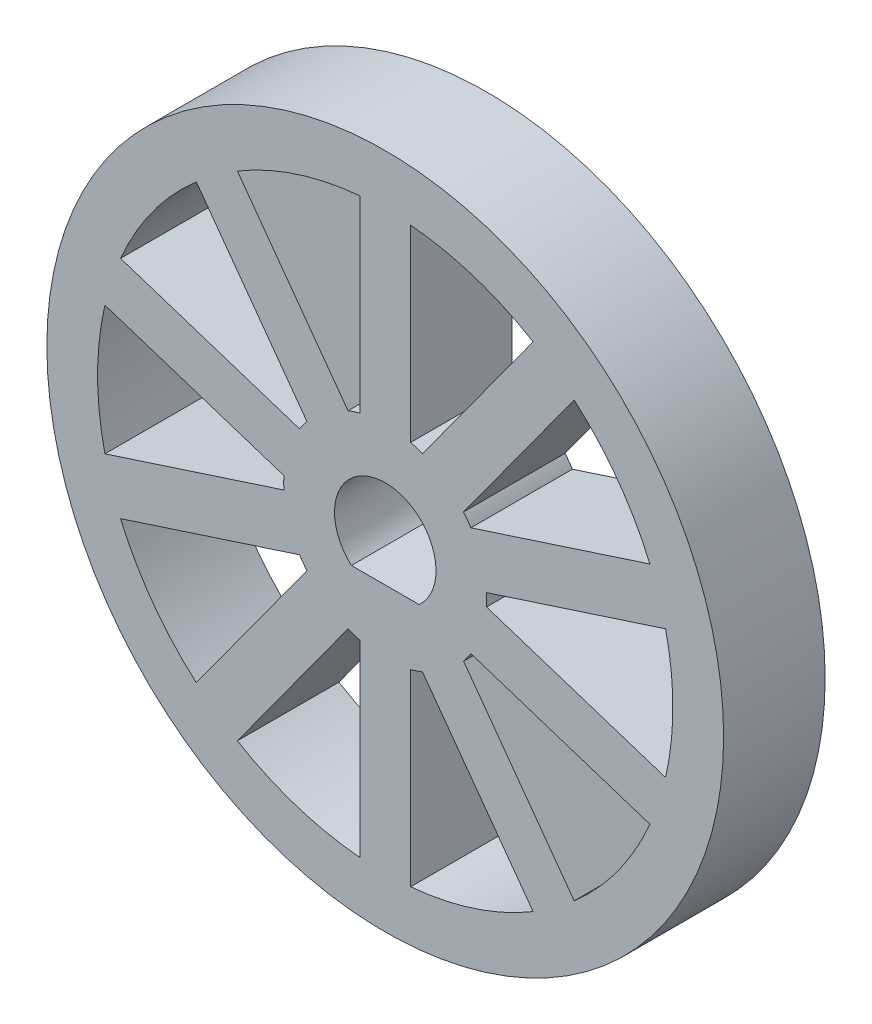
SolidWorks part; units mm, degrees
ref_plane "Front Plane" through (0, 0, 0) normal (0, 0, 1) x (1, 0, 0)
ref_plane "Top Plane" through (0, 0, 0) normal (0, 1, 0) x (1, 0, 0)
ref_plane "Right Plane" through (0, 0, 0) normal (1, 0, 0) x (0, 0, -1)
sketch "Sketch1" plane through (0, 0, 0) normal (0, 0, 1) x (1, 0, 0)
  line L0 (-2, -2.2361) -> (2, -2.2361)
  line L1 (-16.5684, -3.8062) -> (-5.9887, -0.3686)
  line L3 (-1.5, -16.9337) -> (-1.5, -5.8095)
  line L5 (1.5, -16.9337) -> (1.5, -5.8095)
  line L6 (-1.5, 5.8095) -> (-1.5, 16.9337)
  line L7 (-5.0616, 3.2218) -> (-15.6414, 6.6594)
  line L9 (-15.6414, -6.6594) -> (-5.0616, -3.2218)
  line L11 (-8.7399, 14.5813) -> (-2.2012, 5.5816)
  line L13 (-11.1669, 12.818) -> (-4.6282, 3.8183)
  line L15 (11.1669, 12.818) -> (4.6282, 3.8183)
  line L17 (8.7399, 14.5813) -> (2.2012, 5.5816)
  line L19 (15.6414, -6.6594) -> (5.0616, -3.2218)
  line L21 (16.5684, -3.8062) -> (5.9887, -0.3686)
  line L28 (-5.9887, 0.3686) -> (-16.5684, 3.8062)
  line L29 (-4.6282, -3.8183) -> (-11.1669, -12.818)
  line L32 (-2.2012, -5.5816) -> (-8.7399, -14.5813)
  line L33 (2.2012, -5.5816) -> (8.7399, -14.5813)
  line L36 (4.6282, -3.8183) -> (11.1669, -12.818)
  line L37 (5.9887, 0.3686) -> (16.5684, 3.8062)
  line L40 (5.0616, 3.2218) -> (15.6414, 6.6594)
  line L41 (1.5, 5.8095) -> (1.5, 16.9337)
  circle A0 centre (0, 0) radius 20
  arc A1 (2, -2.2361) -> (-2, -2.2361) centre (0, 0) ccw
  arc A2 (-16.5684, 3.8062) -> (-16.5684, -3.8062) centre (0, 0) ccw
  arc A3 (-5.9887, 0.3686) -> (-5.9887, -0.3686) centre (0, 0) ccw
  arc A4 (-15.6414, -6.6594) -> (-11.1669, -12.818) centre (0, 0) ccw
  arc A5 (-8.7399, -14.5813) -> (-1.5, -16.9337) centre (0, 0) ccw
  arc A6 (1.5, -16.9337) -> (8.7399, -14.5813) centre (0, 0) ccw
  arc A7 (11.1669, -12.818) -> (15.6414, -6.6594) centre (0, 0) ccw
  arc A8 (16.5684, -3.8062) -> (16.5684, 3.8062) centre (0, 0) ccw
  arc A9 (15.6414, 6.6594) -> (11.1669, 12.818) centre (0, 0) ccw
  arc A10 (8.7399, 14.5813) -> (1.5, 16.9337) centre (0, 0) ccw
  arc A11 (-1.5, 16.9337) -> (-8.7399, 14.5813) centre (0, 0) ccw
  arc A12 (-11.1669, 12.818) -> (-15.6414, 6.6594) centre (0, 0) ccw
  arc A13 (-5.0616, -3.2218) -> (-4.6282, -3.8183) centre (0, 0) ccw
  arc A14 (-1.5, 5.8095) -> (-2.2012, 5.5816) centre (0, 0) ccw
  arc A15 (2.2012, 5.5816) -> (1.5, 5.8095) centre (0, 0) ccw
  arc A16 (5.0616, 3.2218) -> (4.6282, 3.8183) centre (0, 0) ccw
  arc A17 (5.9887, -0.3686) -> (5.9887, 0.3686) centre (0, 0) ccw
  arc A18 (4.6282, -3.8183) -> (5.0616, -3.2218) centre (0, 0) ccw
  arc A19 (1.5, -5.8095) -> (2.2012, -5.5816) centre (0, 0) ccw
  arc A20 (-2.2012, -5.5816) -> (-1.5, -5.8095) centre (0, 0) ccw
  arc A21 (-4.6282, 3.8183) -> (-5.0616, 3.2218) centre (0, 0) ccw
  point P30 (0, 0)
  dimension "D1" = 40
  dimension "D2" = 6
  dimension "D3" = 3
  dimension "D4" = 3
  dimension "D5" = 4
  dimension "D6" = 5
extrude "Boss-Extrude1" add sketch "Sketch1" along normal blind 6
